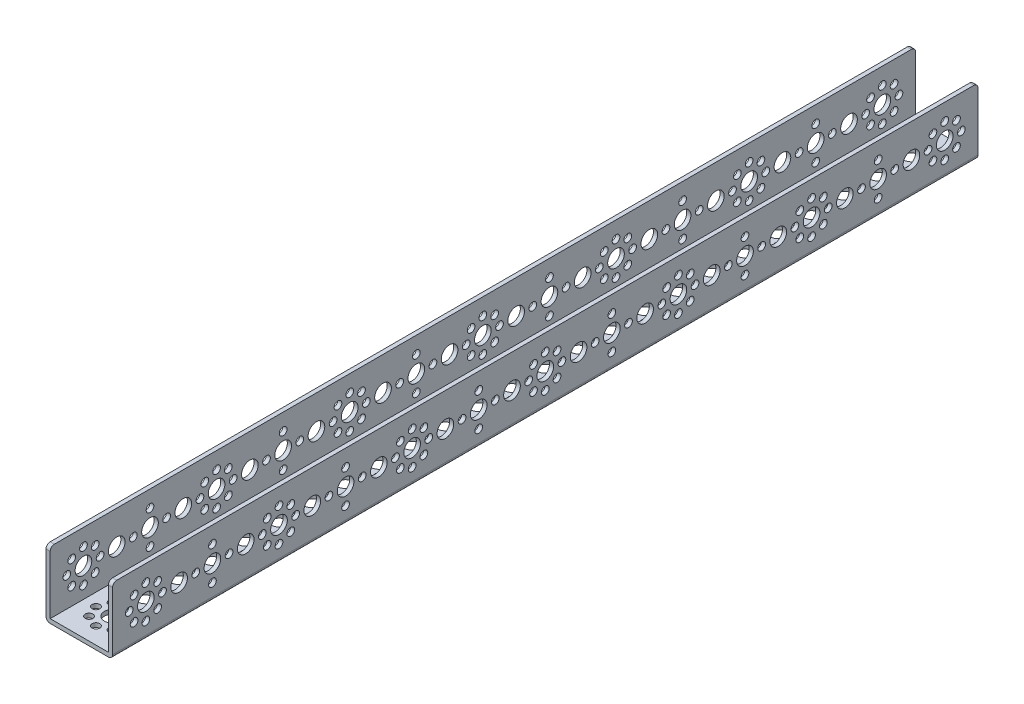
SolidWorks part; units mm, degrees
other "Defeature"
material "5052 Alloy"
ref_plane "Front Plane" through (0, 0, 0) normal (0, 0, 1) x (1, 0, 0)
ref_plane "Top Plane" through (0, 0, 0) normal (0, 1, 0) x (1, 0, 0)
ref_plane "Right Plane" through (0, 0, 0) normal (1, 0, 0) x (0, 0, -1)
sketch "Sketch1" plane through (0, 0, 0) normal (0, 0, 1) x (1, 0, 0)
  line L0 (-14, 0) -> (14, 0)
  line L1 (16, 2) -> (16, 32)
  line L2 (16, 32) -> (14, 32)
  line L3 (14, 32) -> (14, 2)
  line L4 (14, 2) -> (-14, 2)
  line L5 (-14, 2) -> (-14, 32)
  line L6 (-14, 32) -> (-16, 32)
  line L7 (-16, 32) -> (-16, 2)
  arc A0 (-16, 2) -> (-14, 0) centre (-14, 2) ccw
  arc A1 (16, 2) -> (14, 0) centre (14, 2) cw
  point P11 (0, 0)
  point P14 (16, 0)
  point P15 (0, 0)
  dimension "D6" = 2
  dimension "D1" = 32
  dimension "D2" = 2
  dimension "D3" = 2
  dimension "D4" = 32
  dimension "D5" = 2
extrude "Boss-Extrude1" add sketch "Sketch1" against normal mid plane 416
sketch "Sketch2" plane through (16, 0, 0) normal (1, 0, 0) x (0, 0, -1)
  line L0 (208, 32) -> (-208, 32) construction
  point P2 (0, 32)
  circle B0 centre (-160, 16) radius 4
  circle B1 centre (-152, 16) radius 1.85
  circle B2 centre (-168, 16) radius 1.85
  circle B3 centre (-160, 8) radius 1.85
  circle B4 centre (-160, 24) radius 1.85
  circle B5 centre (-176, 16) radius 4
  circle B6 centre (-144, 16) radius 4
  circle B7 centre (-112, 16) radius 4
  circle B8 centre (-80, 16) radius 4
  circle B9 centre (-186.3431, 21.6569) radius 1.85
  circle B10 centre (-192, 24) radius 1.85
  circle B11 centre (-197.6569, 21.6569) radius 1.85
  circle B12 centre (-192, 16) radius 4
  circle B13 centre (-184, 16) radius 1.85
  circle B14 centre (-200, 16) radius 1.85
  circle B15 centre (-192, 8) radius 1.85
  circle B16 centre (-186.3431, 10.3431) radius 1.85
  circle B17 centre (-197.6569, 10.3431) radius 1.85
  circle B18 centre (-96, 16) radius 4
  circle B19 centre (-88, 16) radius 1.85
  circle B20 centre (-104, 16) radius 1.85
  circle B21 centre (-96, 8) radius 1.85
  circle B22 centre (-96, 24) radius 1.85
  circle B23 centre (-128, 16) radius 4
  circle B24 centre (-120, 16) radius 1.85
  circle B25 centre (-136, 16) radius 1.85
  circle B26 centre (-128, 8) radius 1.85
  circle B27 centre (-128, 24) radius 1.85
  circle B28 centre (-133.6569, 21.6569) radius 1.85
  circle B29 centre (-122.3431, 21.6569) radius 1.85
  circle B30 centre (-122.3431, 10.3431) radius 1.85
  circle B31 centre (-133.6569, 10.3431) radius 1.85
  circle B32 centre (-160, 16) radius 8 construction
  line B33 (-197.6569, 21.6569) -> (-186.3431, 10.3431) construction
  line B34 (-197.6569, 10.3431) -> (-186.3431, 21.6569) construction
  line B35 (-192, 16) -> (-192, 8) construction
  circle B36 centre (-192, 16) radius 8 construction
  circle B37 centre (-48, 16) radius 4
  circle B38 centre (-56, 16) radius 1.85
  circle B39 centre (-64, 8) radius 1.85
  circle B40 centre (-64, 16) radius 4
  circle B41 centre (-64, 24) radius 1.85
  circle B42 centre (-69.6569, 21.6569) radius 1.85
  circle B43 centre (-69.6569, 10.3431) radius 1.85
  circle B44 centre (-72, 16) radius 1.85
  circle B45 centre (-58.3431, 21.6569) radius 1.85
  circle B46 centre (-58.3431, 10.3431) radius 1.85
  circle B47 centre (8, 16) radius 1.85
  circle B48 centre (0, 8) radius 1.85
  circle B49 centre (0, 16) radius 4
  circle B50 centre (0, 24) radius 1.85
  circle B51 centre (-5.6569, 21.6569) radius 1.85
  circle B52 centre (-5.6569, 10.3431) radius 1.85
  circle B53 centre (-8, 16) radius 1.85
  circle B54 centre (5.6569, 21.6569) radius 1.85
  circle B55 centre (5.6569, 10.3431) radius 1.85
  circle B56 centre (-32, 16) radius 4
  circle B57 centre (-24, 16) radius 1.85
  circle B58 centre (-40, 16) radius 1.85
  circle B59 centre (-32, 8) radius 1.85
  circle B60 centre (-32, 24) radius 1.85
  circle B61 centre (-16, 16) radius 4
  dimension "D1" = 16
sketch_block_instance "Block6-1"
sketch_block "Block6" parameters "D8"=8, "D1"=16, "D2"=16, "D3"=16, "D4"=16, "D5"=16, "D6"=16, "D7"=16, "D9"=19.6738, "D10"=21.0194, "D11"=21.9372, "D12"=19.473, "D13"=17.0626
sketch_block_instance "Block5-1"
sketch_block "Block5" parameters "D1"=16, "D2"=3.7, "D3"=8
sketch_block_instance "Block2-4"
sketch_block "Block2" parameters "D1"=3.7, "D2"=16, "D3"=8, "D4"=8
sketch_block_instance "Block5-2"
sketch_block_instance "Block2-5"
sketch_block_instance "Block2-11"
sketch_block_instance "Block2-12"
sketch_block_instance "Block5-4"
extrude "Cut-Extrude1" cut sketch "Sketch2" against normal through all
sketch "Sketch5" plane through (0, 0, 0) normal (0, -1, 0) x (1, 0, 0)
  line L0 (-14, 208) -> (14, 208) construction
  line L1 (0, 32) -> (0, 0) construction
  line L2 (0, 32) -> (0, 64) construction
  line L3 (-14, -208) -> (-14, 208) construction
  line L4 (0, 64) -> (0, 96) construction
  line L5 (0, 96) -> (0, 128) construction
  line L6 (0, 128) -> (0, 160) construction
  line L7 (0, 160) -> (0, 192) construction
  circle A0 centre (0, 16) radius 4
  circle A1 centre (0, 48) radius 4
  circle A2 centre (0, 80) radius 4
  circle A3 centre (0, 112) radius 4
  circle A4 centre (0, 144) radius 4
  circle A5 centre (0, 176) radius 4
  point P2 (0, 208)
  point P5 (-14, 0)
  circle B0 centre (0, 160) radius 4
  circle B1 centre (0, 152) radius 1.85
  circle B2 centre (0, 168) radius 1.85
  circle B3 centre (-8, 160) radius 1.85
  circle B4 centre (8, 160) radius 1.85
  circle B5 centre (0, 184) radius 1.85
  circle B6 centre (-8, 192) radius 1.85
  circle B7 centre (0, 192) radius 4
  circle B8 centre (8, 192) radius 1.85
  circle B9 centre (5.6569, 197.6569) radius 1.85
  circle B10 centre (-5.6569, 197.6569) radius 1.85
  circle B11 centre (0, 200) radius 1.85
  circle B12 centre (5.6569, 186.3431) radius 1.85
  circle B13 centre (-5.6569, 186.3431) radius 1.85
  circle B14 centre (0, 96) radius 4
  circle B15 centre (0, 88) radius 1.85
  circle B16 centre (0, 104) radius 1.85
  circle B17 centre (-8, 96) radius 1.85
  circle B18 centre (8, 96) radius 1.85
  circle B19 centre (0, 120) radius 1.85
  circle B20 centre (-8, 128) radius 1.85
  circle B21 centre (0, 128) radius 4
  circle B22 centre (8, 128) radius 1.85
  circle B23 centre (5.6569, 133.6569) radius 1.85
  circle B24 centre (-5.6569, 133.6569) radius 1.85
  circle B25 centre (0, 136) radius 1.85
  circle B26 centre (5.6569, 122.3431) radius 1.85
  circle B27 centre (-5.6569, 122.3431) radius 1.85
  circle B28 centre (0, 56) radius 1.85
  circle B29 centre (-8, 64) radius 1.85
  circle B30 centre (0, 64) radius 4
  circle B31 centre (8, 64) radius 1.85
  circle B32 centre (5.6569, 69.6569) radius 1.85
  circle B33 centre (-5.6569, 69.6569) radius 1.85
  circle B34 centre (0, 72) radius 1.85
  circle B35 centre (5.6569, 58.3431) radius 1.85
  circle B36 centre (-5.6569, 58.3431) radius 1.85
  circle B37 centre (0, -8) radius 1.85
  circle B38 centre (-8, 0) radius 1.85
  circle B39 centre (0, 0) radius 4
  circle B40 centre (8, 0) radius 1.85
  circle B41 centre (5.6569, 5.6569) radius 1.85
  circle B42 centre (-5.6569, 5.6569) radius 1.85
  circle B43 centre (0, 8) radius 1.85
  circle B44 centre (5.6569, -5.6569) radius 1.85
  circle B45 centre (-5.6569, -5.6569) radius 1.85
  circle B46 centre (0, 32) radius 4
  circle B47 centre (0, 24) radius 1.85
  circle B48 centre (0, 40) radius 1.85
  circle B49 centre (-8, 32) radius 1.85
  circle B50 centre (8, 32) radius 1.85
  dimension "D2" = 8
  dimension "D1" = 32
sketch_block_instance "Block5-5"
sketch_block_instance "Block2-13"
sketch_block_instance "Block5-6"
sketch_block_instance "Block2-14"
sketch_block_instance "Block2-15"
sketch_block_instance "Block2-16"
sketch_block_instance "Block5-7"
extrude "Cut-Extrude2" cut sketch "Sketch5" against normal up to surface (2 mm away) up to face at (0, 2, 0)
fillet "Fillet1" radius 2 4 edges at (15, 32, 208) (-15, 32, -208) (15, 32, -208) (-15, 32, 208)
mirror "Mirror1" about plane through (0, 0, 0) normal (0, 0, 1) of "Cut-Extrude2", "Cut-Extrude1"
